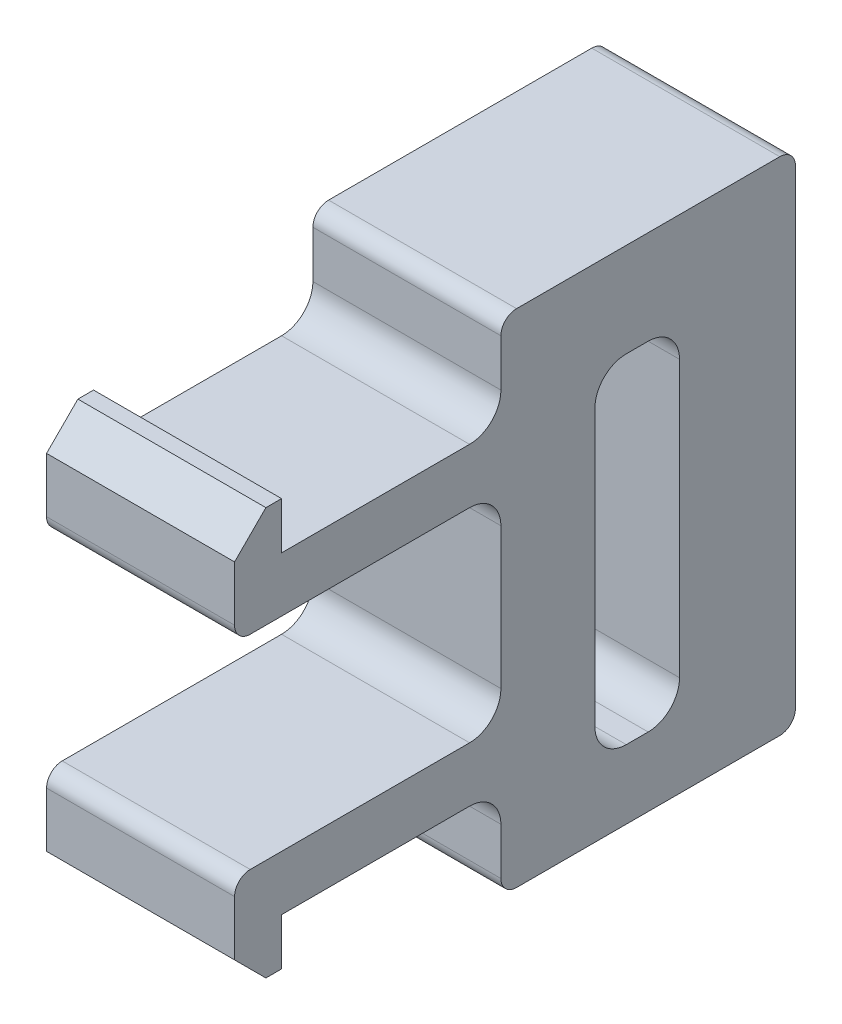
SolidWorks part; units mm, degrees
material "Delrin 2700 NC010, Low Viscosity Acetal Copolymer (SS)"
ref_plane "Plan de face" through (0, 0, 0) normal (0, 0, 1) x (1, 0, 0)
ref_plane "Plan de dessus" through (0, 0, 0) normal (0, 1, 0) x (1, 0, 0)
ref_plane "Plan de droite" through (0, 0, 0) normal (1, 0, 0) x (0, 0, -1)
sketch "Esquisse1" plane through (0, 0, 0) normal (0, 0, 1) x (1, 0, 0)
  line L0 (52.8, 45.5898) -> (52.8, 29.5898)
  line L3 (52.8, 29.5898) -> (58.8, 29.5898)
  line L4 (58.8, 29.5898) -> (58.8, 45.5898)
  line L5 (58.8, 45.5898) -> (52.8, 45.5898)
  line L6 (55.8, 42.4523) -> (55.8, 32.7471) construction
  dimension "D1" = 6
  dimension "D2" = 16
extrude "Extrusion1" add sketch "Esquisse1" along normal blind 3.7
sketch "Esquisse2" plane through (0, 0, 3.7) normal (0, 0, 1) x (1, 0, 0)
  line L0 (52.8, 45.5898) -> (52.8, 42.5898)
  line L1 (52.8, 45.5898) -> (58.8, 45.5898)
  line L2 (52.8, 42.5898) -> (58.8, 42.5898)
  line L3 (58.8, 45.5898) -> (58.8, 42.5898)
  line L4 (52.8, 45.5898) -> (52.8, 29.5898) construction
  line L5 (58.8, 29.5898) -> (58.8, 45.5898) construction
  line L6 (55.8, 29.5898) -> (55.8, 31.7898)
  line L7 (55.8, 29.5898) -> (58.8, 29.5898)
  line L8 (55.8, 31.7898) -> (58.8, 31.7898)
  line L9 (58.8, 29.5898) -> (58.8, 31.7898)
  dimension "D1" = 3
  dimension "D2" = 2.2
  dimension "D3" = 3
extrude "Extrusion2" add sketch "Esquisse2" along normal blind 2.7
sketch "Esquisse3" plane through (0, 0, 3.7) normal (0, 0, 1) x (1, 0, 0)
  line L0 (52.8, 29.5898) -> (55.8, 29.5898)
  line L1 (52.8, 29.5898) -> (52.8, 40.5898)
  line L2 (55.8, 29.5898) -> (55.8, 40.5898)
  line L3 (52.8, 40.5898) -> (55.8, 40.5898)
  line L4 (52.8, 29.5898) -> (55.8, 29.5898) construction
  line L5 (55.8, 31.7898) -> (55.8, 29.5898) construction
  dimension "D1" = 11
extrude "Enlèv. mat.-Extru.1" cut sketch "Esquisse3" against normal blind 5
sketch "Esquisse4" plane through (0, 0, 6.4) normal (0, 0, 1) x (1, 0, 0)
  line L0 (52.8, 45.5898) -> (52.8, 29.5898)
  line L1 (52.8, 45.5898) -> (58.8, 45.5898)
  line L2 (58.8, 45.5898) -> (58.8, 29.5898)
  line L3 (58.8, 29.5898) -> (52.8, 29.5898)
extrude "Extrusion3" add sketch "Esquisse4" along normal blind 3
sketch "Esquisse5" plane through (52.8, 0, 0) normal (-1, 0, 0) x (0, 0, 1)
  line L0 (9.4, 37.5898) -> (12.3106, 37.5898) construction
  line L1 (9.4, 45.5898) -> (9.4, 29.5898) construction
  line L2 (8.1832, 42.5898) -> (16.4, 42.5898)
  line L4 (17.9, 44.0898) -> (17.9, 40.8398)
  line L5 (8.1832, 32.5898) -> (16.4, 32.5898)
  line L6 (16.4, 42.5898) -> (16.4, 44.0898)
  line L7 (16.4, 44.0898) -> (17.9, 44.0898)
  line L8 (16.4, 32.5898) -> (16.4, 31.0898)
  line L9 (16.4, 31.0898) -> (17.9, 31.0898)
  line L10 (17.9, 40.8398) -> (9.2, 40.8398)
  line L11 (8.1832, 42.5898) -> (8.1832, 32.5898)
  line L12 (9.2, 40.8398) -> (9.2, 34.3398)
  line L13 (17.9, 34.3398) -> (9.2, 34.3398)
  line L15 (17.9, 34.3398) -> (17.9, 31.0898)
  dimension "D1" = 10
  dimension "D2" = 1.5
  dimension "D3" = 1.5
  dimension "D4" = 6.5
  dimension "D5" = 8.5
  dimension "D6" = 8.7
  dimension "D7" = 1.5
extrude "Extrusion4" add sketch "Esquisse5" along direction (-1, 0, 0) on the side against the normal up to surface (6 mm away)
chamfer "Chanfrein1" distance 1 angle 45 2 edges at (55.8, 31.0898, 17.9) (55.8, 44.0898, 17.9)
fillet "Congé1" radius 1 9 edges at (55.8, 40.5898, 1.85) (55.8, 42.5898, 6.4) (57.3, 31.7898, 3.7) (57.3, 31.7898, 6.4) (55.8, 34.3398, 9.4) (55.8, 42.5898, 9.4) (55.8, 32.5898, 9.4) (55.8, 40.8398, 9.4)
fillet "Congé2" radius 0.5 6 edges at (55.8, 34.3398, 17.9) (55.8, 40.8398, 17.9) (55.8, 45.5898, 9.4) (55.8, 45.5898, 0) (55.8, 29.5898, 9.4) (57.3, 29.5898, 0)
sketch "Esquisse6" plane through (0, 0, 0) normal (0, 0, -1) x (-1, 0, 0)
  line L0 (-56.8, 29.5898) -> (-52.3818, 46.0786)
  line L1 (-55.8, 29.5898) -> (-58.8, 29.5898) construction
  line L2 (-58.8, 30.0898) -> (-58.8, 45.0898) construction
  line L3 (-52.8, 29.5898) -> (-55.8, 29.5898) construction
  line L4 (-56.8, 29.5898) -> (-52.3818, 29.5898)
  line L5 (-52.3818, 29.5898) -> (-52.3818, 46.0786)
  dimension "D1" = 2
  dimension "D2" = 75
extrude "Enlèv. mat.-Extru.2" cut sketch "Esquisse6" against normal up to surface (6.4 mm away) up to face at (55.8, 34.6564, 6.4)
